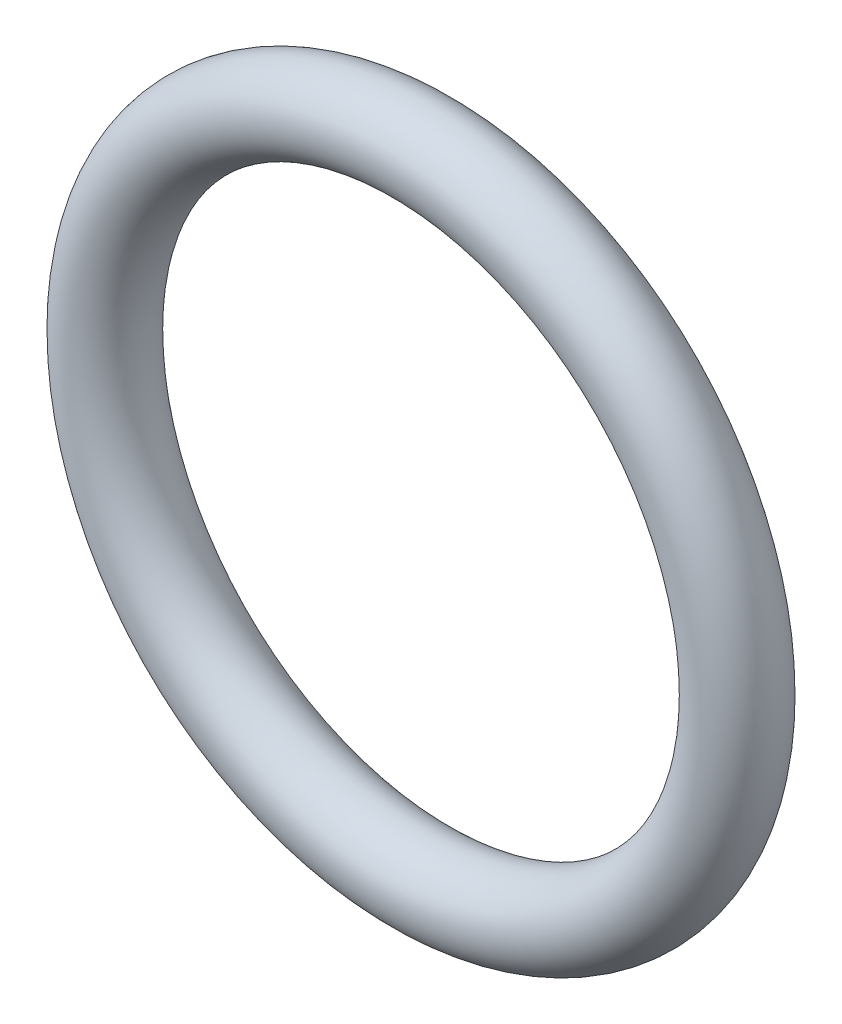
SolidWorks part; units mm, degrees
material "Silicon Rubber"
ref_plane "Front Plane" through (0, 0, 0) normal (0, 0, 1) x (1, 0, 0)
ref_plane "Top Plane" through (0, 0, 0) normal (0, 1, 0) x (1, 0, 0)
ref_plane "Right Plane" through (0, 0, 0) normal (1, 0, 0) x (0, 0, -1)
sketch "Sketch1" plane through (0, 0, 0) normal (0, 1, 0) x (1, 0, 0)
  line L0 (0, 25.1616) -> (0, -25.6031) construction
  line L1 (0, 0) -> (12.3825, 0) construction
  line L2 (12.3825, 0) -> (14.224, 0) construction
  circle A0 centre (14.224, 0) radius 1.8415
  dimension "D2" = 3.683
  dimension "D1" = 12.3825
revolve "Revolve1" add sketch "Sketch1" angle 360 about L0
